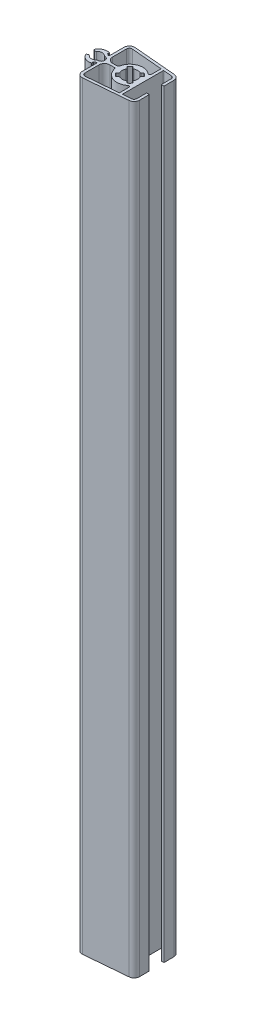
SolidWorks part; units mm, degrees
material "6061-T6 (SS)"
ref_plane "Front Plane" through (0, 0, 0) normal (0, 0, 1) x (1, 0, 0)
ref_plane "Top Plane" through (0, 0, 0) normal (0, 1, 0) x (1, 0, 0)
ref_plane "Right Plane" through (0, 0, 0) normal (1, 0, 0) x (0, 0, -1)
sketch "Sketch1" plane through (0, 0, 0) normal (0, 1, 0) x (1, 0, 0)
  line L0 (-34.9847, 0) -> (34.9847, 0) construction
  line L1 (0, 0) -> (29.9549, 29.9549) construction
  line L2 (-30, -15) -> (30, -15) construction
  line L3 (-30, -15) -> (-30, 15) construction
  line L4 (-30, 15) -> (30, 15) construction
  line L5 (30, -15) -> (30, 15) construction
  line L6 (-30, -15) -> (30, 15) construction
  line L7 (-30, 15) -> (30, -15) construction
  line L8 (0, 3.65) -> (0, 11.7261)
  line L9 (3.2615, 14.7147) -> (27.2615, 12.6149)
  line L10 (30, 9.6263) -> (30, 4.25)
  line L11 (0, 0) -> (0, 32.1354) construction
  line L12 (-1.5, 25.8404) -> (-1.5, -19.4061) construction
  line L13 (22.3, 27.909) -> (22.3, -21.4748) construction
  line L14 (-0.5606, 3.3705) -> (-1.2416, 3.8836)
  line L15 (1.5, 2.6) -> (1.5, 11.7261) construction
  line L16 (1.5, 3.75) -> (1.5, 11.7261)
  line L17 (3.1307, 13.2204) -> (20.6631, 11.6865)
  line L18 (28.5, 9.6263) -> (28.5, 4.25)
  line L19 (1.5, 2.6) -> (-1.5, 2.6) construction
  line L20 (-3.5, 0) -> (-16.4721, 7.4894) construction
  line L21 (22.3, -11.3796) -> (22.3, 11.3796)
  line L22 (20.8, 11.5371) -> (20.8, 6.269)
  line L23 (-3.5, 0) -> (-18.1368, -8.4505) construction
  line L24 (22.4631, 11.529) -> (27.1307, 11.1206)
  line L25 (29.85, 4.1) -> (28.65, 4.1)
  line L26 (3.1307, 13.2204) -> (27.1307, 11.1206) construction
  line L27 (0, -3.65) -> (0, -11.7261)
  line L28 (29.85, -4.1) -> (28.65, -4.1)
  line L29 (22.4631, -11.529) -> (27.1307, -11.1206)
  line L30 (28.5, -9.6263) -> (28.5, -4.25)
  line L31 (3.1307, -13.2204) -> (20.6631, -11.6865)
  line L32 (1.5, -3.75) -> (1.5, -11.7261)
  line L33 (30, -9.6263) -> (30, -4.25)
  line L34 (3.2615, -14.7147) -> (27.2615, -12.6149)
  line L35 (-6.682, 1.8371) -> (-7.2374, 2.1578)
  line L36 (11.9524, 4.7447) -> (12.5546, 4.1425)
  line L37 (10.2553, 3.0476) -> (10.8575, 2.4454)
  line L38 (19.7447, 3.0476) -> (19.1425, 2.4454)
  line L39 (18.0476, 4.7447) -> (17.4454, 4.1425)
  line L40 (18.0476, -4.7447) -> (17.4454, -4.1425)
  line L41 (19.7447, -3.0476) -> (19.1425, -2.4454)
  line L42 (10.2553, -3.0476) -> (10.8575, -2.4454)
  line L43 (11.9524, -4.7447) -> (12.5546, -4.1425)
  line L44 (20.8, -6.269) -> (20.8, -11.5371)
  line L45 (4.5, 0.75) -> (7.091, 0.75)
  line L46 (4.5, -0.75) -> (7.091, -0.75)
  line L47 (28.5, 9.6263) -> (28.5, 4.1) construction
  line L48 (-6.682, -1.8371) -> (-7.2374, -2.1578)
  line L49 (-0.75, 22.5195) -> (-0.75, -32.6531) construction
  line L50 (30, 9.6263) -> (30, 4.1) construction
  line L51 (-34.9847, -2) -> (34.9847, -2) construction
  line L52 (-1.5, 4.1167) -> (-1.5, 4.8952)
  line L53 (0, 4.1) -> (0, 11.7261) construction
  line L54 (-1.5, -4.1167) -> (-1.5, -4.8952)
  line L55 (0, 4.1) -> (-1.5, 4.1) construction
  line L56 (-0.5606, -3.3705) -> (-1.2416, -3.8836)
  line L57 (-34.9847, 2) -> (34.9847, 2) construction
  line L58 (23.8, -11.412) -> (23.8, 11.412) construction
  line L59 (23.8, -11.3796) -> (23.8, 11.3796) construction
  arc A0 (30, 9.6263) -> (27.2615, 12.6149) centre (27, 9.6263) ccw
  arc A1 (0, 11.7261) -> (3.2615, 14.7147) centre (3, 11.7261) cw
  arc A2 (1.5, 11.7261) -> (3.1307, 13.2204) centre (3, 11.7261) cw
  arc A3 (28.5, 9.6263) -> (27.1307, 11.1206) centre (27, 9.6263) ccw
  arc A4 (28.5, -9.6263) -> (27.1307, -11.1206) centre (27, -9.6263) cw
  arc A5 (1.5, -11.7261) -> (3.1307, -13.2204) centre (3, -11.7261) ccw
  arc A6 (0, -11.7261) -> (3.2615, -14.7147) centre (3, -11.7261) ccw
  arc A7 (30, -9.6263) -> (27.2615, -12.6149) centre (27, -9.6263) cw
  arc A8 (19.5795, 5.6849) -> (7.8279, 1.3602) centre (15, 0) ccw
  circle A9 centre (15, 0) radius 5.8 construction
  arc A10 (11.0212, 1.6307) -> (11.0212, -1.6307) centre (15, 0) ccw
  arc A11 (11.6971, 4.7677) -> (10.2323, 3.3029) centre (15, 0) ccw
  arc A12 (16.6307, 3.9788) -> (13.3693, 3.9788) centre (15, 0) ccw
  arc A13 (11.0212, 1.6307) -> (10.8575, 2.4454) centre (10.3272, 1.9151) ccw
  arc A14 (13.3693, 3.9788) -> (12.5546, 4.1425) centre (13.0849, 4.6728) cw
  arc A15 (11.6971, 4.7677) -> (11.9524, 4.7447) centre (11.811, 4.6033) cw
  arc A16 (10.2553, 3.0476) -> (10.2323, 3.3029) centre (10.3967, 3.189) cw
  arc A17 (19.7447, 3.0476) -> (19.7677, 3.3029) centre (19.6033, 3.189) ccw
  arc A18 (18.3029, 4.7677) -> (18.0476, 4.7447) centre (18.189, 4.6033) ccw
  arc A19 (16.6307, 3.9788) -> (17.4454, 4.1425) centre (16.9151, 4.6728) ccw
  arc A20 (18.9788, 1.6307) -> (19.1425, 2.4454) centre (19.6728, 1.9151) cw
  arc A21 (18.3029, 4.7677) -> (19.7677, 3.3029) centre (15, 0) cw
  arc A22 (18.9788, 1.6307) -> (18.9788, -1.6307) centre (15, 0) cw
  arc A23 (18.3029, -4.7677) -> (19.7677, -3.3029) centre (15, 0) ccw
  arc A24 (18.9788, -1.6307) -> (19.1425, -2.4454) centre (19.6728, -1.9151) ccw
  arc A25 (16.6307, -3.9788) -> (17.4454, -4.1425) centre (16.9151, -4.6728) cw
  arc A26 (18.3029, -4.7677) -> (18.0476, -4.7447) centre (18.189, -4.6033) cw
  arc A27 (19.7447, -3.0476) -> (19.7677, -3.3029) centre (19.6033, -3.189) cw
  arc A28 (10.2553, -3.0476) -> (10.2323, -3.3029) centre (10.3967, -3.189) ccw
  arc A29 (11.6971, -4.7677) -> (11.9524, -4.7447) centre (11.811, -4.6033) ccw
  arc A30 (13.3693, -3.9788) -> (12.5546, -4.1425) centre (13.0849, -4.6728) ccw
  arc A31 (11.0212, -1.6307) -> (10.8575, -2.4454) centre (10.3272, -1.9151) cw
  arc A32 (16.6307, -3.9788) -> (13.3693, -3.9788) centre (15, 0) cw
  arc A33 (11.6971, -4.7677) -> (10.2323, -3.3029) centre (15, 0) cw
  arc A34 (20.8, 11.5371) -> (20.6631, 11.6865) centre (20.65, 11.5371) ccw
  circle A35 centre (15, 0) radius 7.3 construction
  arc A36 (22.3, 11.3796) -> (22.4631, 11.529) centre (22.45, 11.3796) cw
  arc A37 (20.6631, -11.6865) -> (20.8, -11.5371) centre (20.65, -11.5371) ccw
  arc A38 (22.4631, -11.529) -> (22.3, -11.3796) centre (22.45, -11.3796) cw
  arc A39 (30, -4.25) -> (29.85, -4.1) centre (29.85, -4.25) ccw
  arc A40 (28.5, -4.25) -> (28.65, -4.1) centre (28.65, -4.25) cw
  arc A41 (28.5, 4.25) -> (28.65, 4.1) centre (28.65, 4.25) ccw
  arc A42 (30, 4.25) -> (29.85, 4.1) centre (29.85, 4.25) cw
  arc A43 (7.8279, -1.3602) -> (19.5795, -5.6849) centre (15, 0) ccw
  arc A44 (19.5795, -5.6849) -> (20.8, -6.269) centre (20.05, -6.269) cw
  arc A45 (19.5795, 5.6849) -> (20.8, 6.269) centre (20.05, 6.269) ccw
  arc A46 (7.091, -0.75) -> (7.8279, -1.3602) centre (7.091, -1.5) cw
  arc A47 (7.091, 0.75) -> (7.8279, 1.3602) centre (7.091, 1.5) ccw
  arc A50 (-7.2374, 2.1578) -> (-7.2988, 2.3502) centre (-7.1624, 2.2877) cw
  circle A51 centre (-2.8563, 0.3148) radius 4.8865 construction
  arc A52 (-2.5436, 1.2718) -> (0.9436, -0.4718) centre (-1, 0) ccw construction
  arc A53 (-1.4072, 3.9781) -> (-1.2416, 3.8836) centre (-1.693, 3.2846) cw
  arc A54 (-1.1333, -1.9956) -> (-1.1333, 1.9956) centre (-1, 0) ccw
  arc A55 (-0.7664, -1.9863) -> (-0.7664, 1.9863) centre (-1, 0) ccw construction
  arc A56 (-1.6118, 5.0403) -> (-7.2988, 2.3502) centre (-2.8563, 0.3148) ccw
  arc A57 (-1.5, 4.8952) -> (-1.6118, 5.0403) centre (-1.65, 4.8952) ccw
  arc A58 (0, 3.65) -> (-0.5606, 3.3705) centre (-0.35, 3.65) cw
  arc A59 (-1.4072, 3.9781) -> (-1.5, 4.1167) centre (-1.35, 4.1167) cw
  arc A60 (-7.2374, -2.1578) -> (-7.2988, -2.3502) centre (-7.1624, -2.2877) ccw
  arc A61 (-1.6118, -5.0403) -> (-7.2988, -2.3502) centre (-2.8563, -0.3148) cw
  arc A62 (-5.7456, 1.9893) -> (-6.682, 1.8371) centre (-6.307, 2.4866) cw
  arc A63 (-1.4072, -3.9781) -> (-1.5, -4.1167) centre (-1.35, -4.1167) ccw
  arc A64 (-1.5, -4.8952) -> (-1.6118, -5.0403) centre (-1.65, -4.8952) cw
  arc A65 (-1.4072, -3.9781) -> (-1.2416, -3.8836) centre (-1.693, -3.2846) ccw
  arc A66 (-5.7456, -1.9893) -> (-6.682, -1.8371) centre (-6.307, -2.4866) ccw
  arc A67 (-1.1333, -1.9956) -> (-1.3308, -2.0723) centre (-1.15, -2.245) ccw
  arc A68 (-1.1333, 1.9956) -> (-1.3308, 2.0723) centre (-1.15, 2.245) cw
  arc A69 (1.5, -3.75) -> (4.5, -0.75) centre (4.5, -3.75) cw
  arc A70 (1.5, 3.75) -> (4.5, 0.75) centre (4.5, 3.75) ccw
  arc A71 (0, -3.65) -> (-0.5606, -3.3705) centre (-0.35, -3.65) ccw
  circle A74 centre (-3.5, 0) radius 3 construction
  arc A75 (-1.3308, 2.0723) -> (-5.7456, 1.9893) centre (-3.5, 0) ccw
  arc A76 (-1.3308, -2.0723) -> (-5.7456, -1.9893) centre (-3.5, 0) cw
  point P2 (0, 0)
  point P17 (0, 15)
  point P24 (0, 15)
  point P36 (-34.9847, 0.75)
  point P37 (34.9847, 0.75)
  point P39 (20.8, 27.909)
  point P40 (20.8, -21.4748)
  point P41 (22.3, 0)
  point P44 (0, -15)
  point P63 (20.8, 0)
  point P73 (-24.4226, 22.5195)
  point P95 (-22.7256, 30.5444)
  point P96 (-24.4226, 32.2415)
  point P120 (-22.7256, 24.2165)
  point P121 (-32.4476, 24.2165)
  point P122 (-30.7505, 22.5195)
  point P123 (22.3, 0)
  point P125 (-34.9847, -0.75)
  point P127 (34.9847, -0.75)
  point P128 (-34.9847, 0.75)
  point P129 (34.9847, 0.75)
  point P134 (20.8, 11.6745)
  point P137 (22.3, 11.5433)
  point P140 (20.8, -11.6745)
  point P143 (22.3, -11.5433)
  point P146 (30, -4.1)
  point P149 (28.5, -4.1)
  point P153 (28.5, 4.1)
  point P157 (30, 4.1)
  point P160 (20.8, -4.4328)
  point P165 (7.7386, -0.75)
  point P173 (1.5, 0.75)
  point P174 (-5.05, 0)
  point P179 (-5.05, 0)
  point P181 (-4.3318, -1.0043)
  point P184 (1.931, 2.1343)
  point P187 (0.4966, 1.6958)
  point P190 (-0.9379, 1.2572)
  point P191 (-4, 0)
  point P193 (-0.5406, 3.3275)
  point P197 (-8.1569, 2.4)
  point P201 (-4, 0)
  point P203 (0, 2.8526)
  point P204 (-8.7739, 2.15)
  point P207 (-0.5406, -3.3275)
  point P209 (-8.1569, -2.4)
  point P211 (-1.5, 6.3787)
  point P213 (-7.354, 2.2251)
  point P219 (-1.5, 5.0094)
  point P220 (-6.0981, 1.5)
  point P223 (-1.5, 4.0094)
  point P228 (-7.354, -2.2251)
  point P229 (0, -2.8526)
  point P236 (-5.9249, -1.4)
  point P242 (-1.5, -4.0976)
  point P244 (-1.5, -4.0094)
  point P245 (-1.5, -5.0094)
  point P252 (-1.25, -1.9843)
  point P255 (-1.25, 1.9843)
  dimension "D6" = 3
  dimension "D7" = 30
  dimension "D14" = 11.6
  dimension "D15" = 0.75
  dimension "D16" = 0.2
  dimension "D17" = 4.3
  dimension "D24" = 0.15
  dimension "D25" = 0.75
  dimension "D26" = 0.75
  dimension "D23" = 30
  dimension "D29" = 0.15
  dimension "D31" = 0.35
  dimension "D32" = 0.75
  dimension "D33" = 1
  dimension "D34" = 3.5
  dimension "D30" = 4
  dimension "D35" = 0.75
  dimension "D37" = 37
  dimension "D39" = 2
  dimension "D19" = 6
  dimension "D36" = 0.15
  dimension "D41" = 0.25
  dimension "D42" = 1.5
  dimension "D27" = 0.15
  dimension "D44" = 3
  dimension "D1" = 45
  dimension "D2" = 30
  dimension "Comprimento" = 30
  dimension "D4" = 15
  dimension "D5" = 85
  dimension "D8" = 4.1
  dimension "D9" = 1.5
  dimension "D10" = 7.7
  dimension "D12" = 6.2
  dimension "D13" = 1.5
  dimension "D20" = 2.4
  dimension "D21" = 2.4
  dimension "D28" = 0.75
  dimension "D38" = 2.5
  dimension "D43" = 22.8241
  dimension "D11" = 1.5
  dimension "D18" = 1.5
  dimension "D40" = 2
extrude "Boss-Extrude1" add sketch "Sketch1" along normal blind 425
